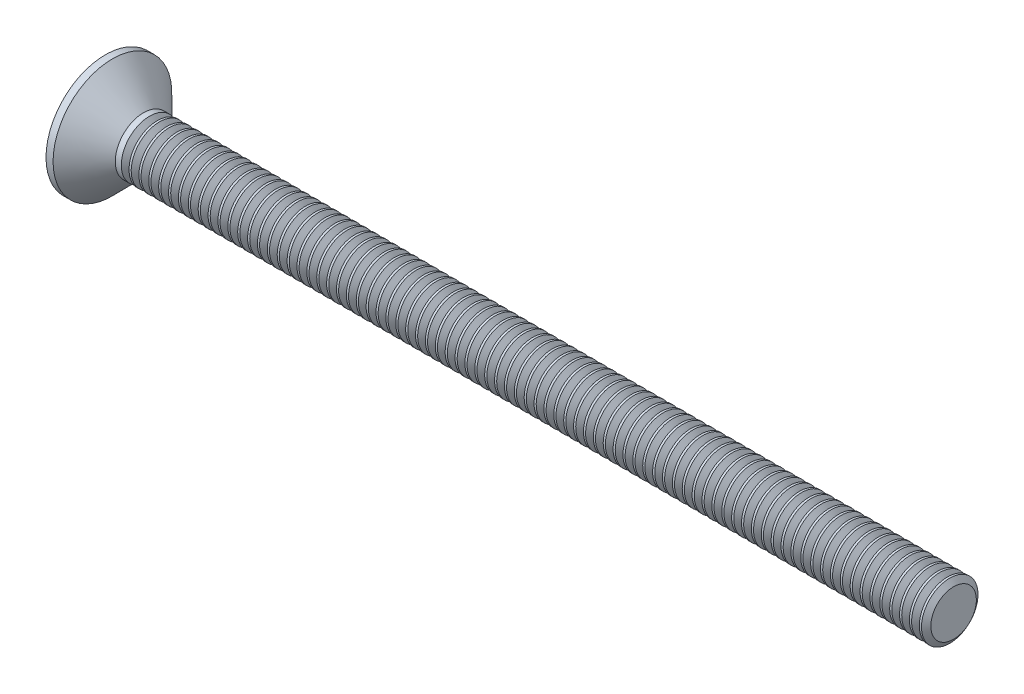
SolidWorks part; units mm, degrees
ref_plane "Plane1" through (0, 0, 0) normal (0, 0, 1) x (1, 0, 0)
ref_plane "Plane2" through (0, 0, 0) normal (0, 1, 0) x (1, 0, 0)
ref_plane "Plane3" through (0, 0, 0) normal (1, 0, 0) x (0, 0, -1)
sketch "BodySke" plane through (0, 0, 0) normal (0, 0, 1) x (1, 0, 0)
  line L0 (0, 0) -> (0, 4.2)
  line L1 (0, 4.2) -> (0.5, 4.2)
  line L2 (2.7, 2) -> (60, 2)
  line L3 (60, 2) -> (60, 0)
  line L4 (60, 0) -> (0, 0)
  line L5 (-6.35, 0) -> (82.55, 0) construction
  line L6 (2.7, -2) -> (60, -2) construction
  line L7 (0.5, -4.2) -> (2.7, -2) construction
  line L8 (0.5, 4.2) -> (2.7, 2)
  line L9 (0, -4.2) -> (0.5, -4.2) construction
  line L10 (3.4, 3.5875) -> (3.4, -5.9375) construction
  line L11 (0, 6.35) -> (0, -3.175) construction
  dimension "Diameter" = 4
  dimension "Length" = 60
  dimension "Head_ht" = 2.7
  dimension "Head_dia" = 8.4
  dimension "Head_ang" = 90
  dimension "D6" = 0.5
  dimension "Advance" = 0.7
  dimension "Thread_nom" = 60
revolve "Base-Revolve" add sketch "BodySke" angle 360 about L5
cosmetic thread "ThreadCosmetic" [suppressed] parameters "Thread_length"=56.6, "Thread_minor"=3.22
sketch "Sketch2" plane through (0, 0, 0) normal (-1, 0, 0) x (0, 0, 1)
  line L0 (-4.2, -0.75) -> (4.2, -0.75)
  line L1 (-4.2, -0.75) -> (-4.2, 0.75)
  line L2 (4.2, 0.75) -> (-4.2, 0.75)
  line L3 (4.2, 0.75) -> (4.2, -0.75)
  dimension "D1" = 0.75
  dimension "Slot_width" = 1.5
  dimension "D2" = 8.4
  dimension "D3" = 4.2
extrude "Slot" [suppressed] cut sketch "Sketch2" against normal blind 1.3
sketch "Sketch3" plane through (0, 0, 0) normal (-1, 0, 0) x (0, 0, 1)
  line L0 (-0.48, 2.23) -> (0.48, 2.23)
  line L1 (0.48, 2.23) -> (0.48, -2.23)
  line L2 (0.48, -2.23) -> (-0.48, -2.23)
  line L3 (-0.48, -2.23) -> (-0.48, 2.23)
  dimension "D1" = 2.23
  dimension "Cross_dia" = 4.46
  dimension "D2" = 0.48
  dimension "Cross_width" = 0.96
ref_plane "Plane4" through (2.65, 0, 0) normal (-1, 0, 0) x (0, 0, 1)
sketch "Sketch4" plane through (2.65, 0, 0) normal (-1, 0, 0) x (0, 0, 1)
  line L0 (-0.24, 0.24) -> (0.24, 0.24)
  line L3 (0.24, 0.24) -> (0.24, -0.24)
  line L4 (0.24, -0.24) -> (-0.24, -0.24)
  line L5 (-0.24, -0.24) -> (-0.24, 0.24)
  dimension "D1" = 0.48
  dimension "D2" = 0.48
  dimension "D3" = 0.24
  dimension "D4" = 0.24
loft "Cross" cut profiles "Sketch3", "Sketch4"
pattern_circular "CirPattern1" count 2 every 90 about axis through (0, 0, 0) along (1, 0, 0) of "Cross"
sketch "ThdSchSke" plane through (0, 0, 0) normal (0, 0, 1) x (1, 0, 0)
  line L0 (3.4, -1.61) -> (3.1269, -2)
  line L1 (3.4, -1.61) -> (3.6731, -2)
  line L2 (3.6731, -2) -> (3.6731, -2.5)
  line L3 (-3.175, 0) -> (5.1513, 0) construction
  line L5 (3.6731, -2.5) -> (3.1269, -2.5)
  line L6 (3.1269, -2.5) -> (3.1269, -2)
  line L7 (0, 4.2) -> (0, -4.2) construction
  dimension "Thread_minor" = 3.22
  dimension "Diameter" = 4
  dimension "Start" = 3.4
  dimension "SideAngle" = 55
  dimension "VeeAngle" = 70
  dimension "Overcut" = 5
revolve "ThreadSchematic" cut sketch "ThdSchSke" angle 360 about L3
pattern_linear "ThdSchPat" count 82 spacing 0.6988 along (1, 0, 0) of "ThreadSchematic"
equation "\"D1@Sketch3\" = \"Cross_dia@Sketch3\" / 2"
equation "\"D2@Sketch3\" = \"Cross_width@Sketch3\" / 2"
equation "\"D1@Sketch4\" = \"Cross_width@Sketch3\" *.5"
equation "\"D2@Sketch4\" = \"D1@Sketch4\""
equation "\"D4@Sketch4\" = \"D2@Sketch4\" / 2"
equation "\"D3@Sketch4\" = \"D1@Sketch4\" / 2"
equation "\"D1@Sketch2\" = \"Slot_width@Sketch2\" / 2"
equation "\"D2@Sketch2\" = \"Head_dia@BodySke\""
equation "\"D3@Sketch2\" = \"D2@Sketch2\" / 2"
equation "\"Thread_length@ThreadCosmetic\" = ((sgn( (\"Length@BodySke\" - \"Advance@BodySke\" - \"Head_ht@BodySke\" ) - \"Thread_nom@BodySke\" )-1)*( (\"Length@BodySke\" - \"Advance@BodySke\" - \"Head_ht@BodySke\" ) - \"Thread_nom@BodySke\" ))/-2+ \"Thread_nom@BodySke\""
equation "\"Thread_minor@ThdSchSke\" = \"Thread_minor@ThreadCosmetic\""
equation "\"Diameter@ThdSchSke\" = \"Diameter@BodySke\""
equation "\"Overcut@ThdSchSke\" = \"Diameter@BodySke\" * 1.25"
equation "\"Start@ThdSchSke\" = 0.000001 + \"Length@BodySke\" - \"Thread_length@ThreadCosmetic\"  '---Countersunk---"
equation "\"Num_threads@ThdSchPat\" = int( \"Thread_length@ThreadCosmetic\" / \"Advance@BodySke\" + 0.999 )  + 1"
equation "\"Advance@ThdSchPat\" = \"Thread_length@ThreadCosmetic\" /  (\"Num_threads@ThdSchPat\" - 1) 'relax it"
